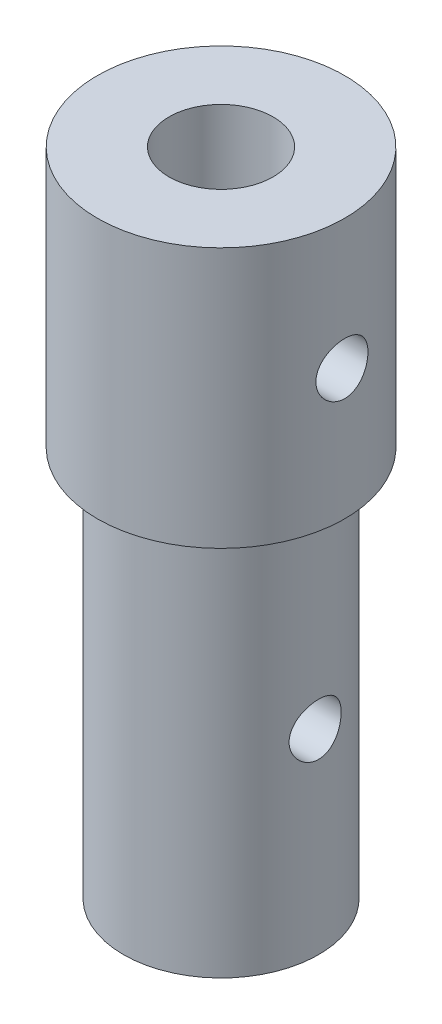
SolidWorks part; units mm, degrees
ref_plane "Front Plane" through (0, 0, 0) normal (0, 0, 1) x (1, 0, 0)
ref_plane "Top Plane" through (0, 0, 0) normal (0, 1, 0) x (1, 0, 0)
ref_plane "Right Plane" through (0, 0, 0) normal (1, 0, 0) x (0, 0, -1)
sketch "Sketch1" plane through (0, 0, 0) normal (0, 1, 0) x (1, 0, 0)
  circle A0 centre (0, 0) radius 7.5
  circle A1 centre (0, 0) radius 2.5
  dimension "D1" = 15
  dimension "D2" = 5
extrude "Boss-Extrude1" add sketch "Sketch1" along normal blind 22
sketch "Sketch2" plane through (0, 22, 0) normal (0, 1, 0) x (1, 0, 0)
  circle A0 centre (0, 0) radius 7.5
  dimension "D1" = 15
extrude "Boss-Extrude2" add sketch "Sketch2" along normal blind 8
sketch "Sketch3" plane through (0, 30, 0) normal (0, 1, 0) x (1, 0, 0)
  circle A0 centre (0, 0) radius 9.5
  dimension "D1" = 19
extrude "Boss-Extrude3" add sketch "Sketch3" along normal blind 20
sketch "Sketch5" plane through (0, 50, 0) normal (0, 1, 0) x (1, 0, 0)
  circle A0 centre (0, 0) radius 4
  dimension "D1" = 8
extrude "Cut-Extrude1" cut sketch "Sketch5" against normal blind 15
sketch "Sketch6" plane through (0, 0, 0) normal (1, 0, 0) x (0, 0, -1)
  line L0 (-7.5, 0) -> (7.5, 0) construction
  line L1 (9.5, 50) -> (-9.5, 50) construction
  circle A0 centre (0, 15) radius 2
  circle A1 centre (0, 40) radius 2
  dimension "D1" = 4
  dimension "D2" = 4
  dimension "D3" = 15
  dimension "D4" = 10
extrude "Cut-Extrude2" cut sketch "Sketch6" along normal blind 17
